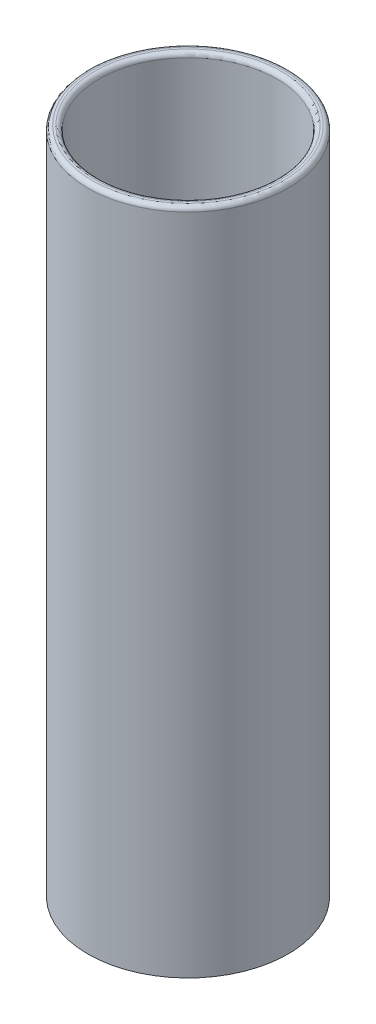
SolidWorks part; units mm, degrees
ref_plane "Front Plane" through (0, 0, 0) normal (0, 0, 1) x (1, 0, 0)
ref_plane "Top Plane" through (0, 0, 0) normal (0, 1, 0) x (1, 0, 0)
ref_plane "Right Plane" through (0, 0, 0) normal (1, 0, 0) x (0, 0, -1)
sketch "Sketch1" plane through (0, 0, 0) normal (0, 1, 0) x (1, 0, 0)
  circle A0 centre (0, 0) radius 22.5
  dimension "D1" = 45
extrude "Boss-Extrude1" add sketch "Sketch1" along normal blind 150
sketch "Sketch2" plane through (0, 150, 0) normal (0, 1, 0) x (1, 0, 0)
  circle A0 centre (0, 0) radius 20
  dimension "D1" = 40
extrude "Cut-Extrude1" cut sketch "Sketch2" against normal blind 140
fillet "Fillet2" radius 1 2 edges at (0, 150, 22.5) (0, 150, 20)
